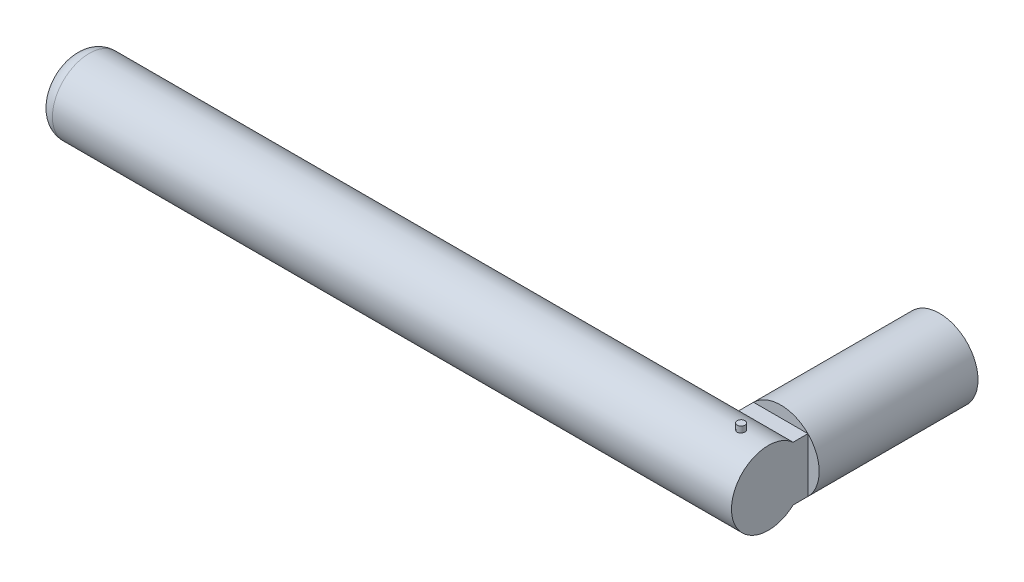
SolidWorks part; units mm, degrees
ref_plane "前视基准面" through (0, 0, 0) normal (0, 0, 1) x (1, 0, 0)
ref_plane "上视基准面" through (0, 0, 0) normal (0, 1, 0) x (1, 0, 0)
ref_plane "右视基准面" through (0, 0, 0) normal (1, 0, 0) x (0, 0, -1)
other "Configuration Table"
sketch "草图1" plane through (0, 0, 0) normal (0, 0, 1) x (1, 0, 0)
  circle A0 centre (0, 0) radius 4.95
  dimension "D1" = 9.9
extrude "凸台-拉伸1" add sketch "草图1" against normal blind 20.44
sketch "草图2" plane through (0, 0, 0) normal (0, 0, 1) x (1, 0, 0)
  line L1 (-3.5002, -3.5002) -> (3.5002, -3.5002)
  line L2 (-3.5002, -3.5002) -> (-3.5002, 3.5002)
  line L3 (-3.5002, 3.5002) -> (3.5002, 3.5002)
  line L4 (3.5002, -3.5002) -> (3.5002, 3.5002)
  line L5 (-3.5002, -3.5002) -> (3.5002, 3.5002) construction
  line L6 (-3.5002, 3.5002) -> (3.5002, -3.5002) construction
  circle A1 centre (0, 0) radius 4.95
  circle A2 centre (0, 0) radius 4.95
  dimension "D1" = 0
extrude "凸台-拉伸2" add sketch "草图2" along normal blind 5.1 contours L1 L4 L3 L2
sketch "草图3" plane through (0, -3.5002, 0) normal (0, -1, 0) x (1, 0, 0)
  line L4 (-3.5002, 0) -> (3.5002, 0)
  line L5 (3.5002, 0) -> (3.5002, 5.1)
  line L6 (3.5002, 5.1) -> (-3.5002, 5.1)
  line L7 (-3.5002, 5.1) -> (-3.5002, 0)
  line L8 (-3.5002, 0) -> (3.5002, 0)
  line L9 (3.5002, 0) -> (3.5002, 5.1)
  line L10 (3.5002, 5.1) -> (-3.5002, 5.1)
  line L11 (-3.5002, 5.1) -> (-3.5002, 0)
  circle A0 centre (0, 5.1) radius 0.5
  dimension "D2" = 1
  dimension "D1" = 0
extrude "凸台-拉伸3" add sketch "草图3" along normal blind 2 and the other way offset from surface (9.0004 mm away) 2 contours L10 A0 | L10 A0 other way up to face at (0, 3.5002, 2.55)
sketch "草图5" plane through (-3.5002, 0, 0) normal (-1, 0, 0) x (0, 0, 1)
  line L4 (0, 3.5002) -> (0, -3.5002)
  line L5 (0, -3.5002) -> (5.1, -3.5002)
  line L6 (5.1, -3.5002) -> (5.1, 3.5002)
  line L7 (5.1, 3.5002) -> (0, 3.5002)
  line L8 (0, 3.5002) -> (0, -3.5002)
  line L9 (0, -3.5002) -> (5.1, -3.5002)
  line L10 (5.1, -3.5002) -> (5.1, 3.5002)
  line L11 (5.1, 3.5002) -> (0, 3.5002)
  circle A0 centre (5.1, 0) radius 4.735
  line M7 (5.1, -3.5002) -> (5.1, 3.5002)
  line M8 (5.1, 3.5002) -> (0, 3.5002)
  dimension "D2" = 9.47
  dimension "D1" = 0
extrude "凸台-拉伸4" add sketch "草图5" along normal blind 82.4 and the other way up to surface contours L9 A0 M8 M7 | A0 L9 M8 M7 other way up to face at (3.5002, 0, 2.55)
fillet "圆角1" radius 2 1 edges at (-85.9002, 0, 9.835)
